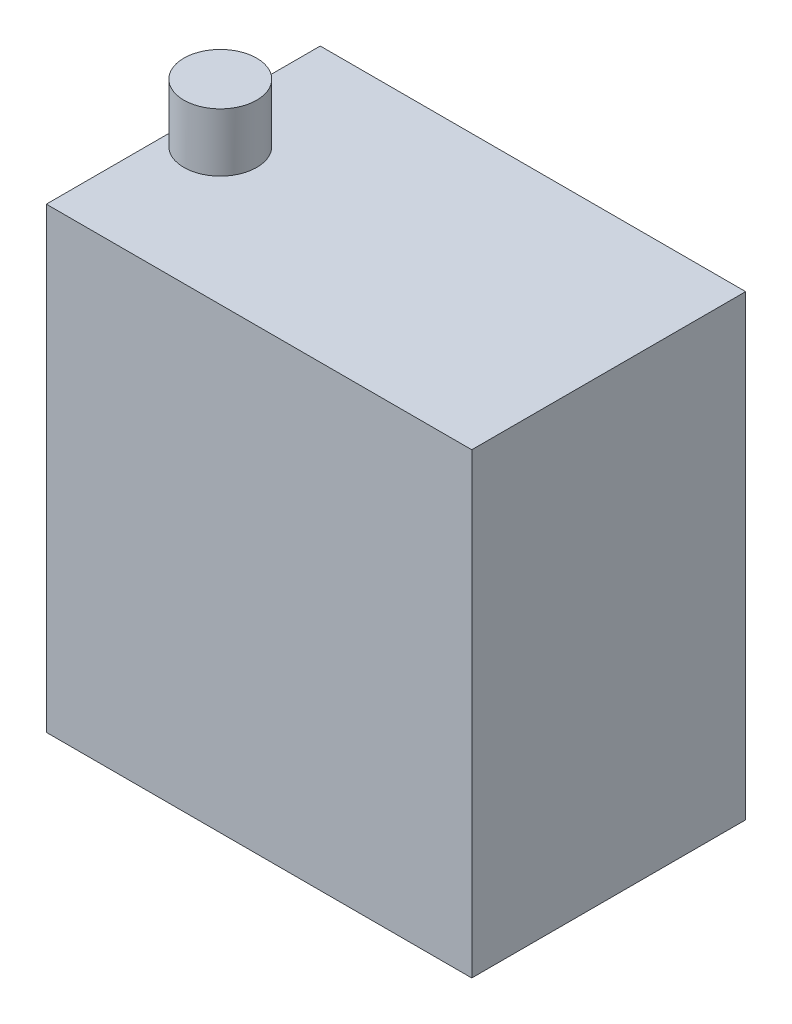
SolidWorks part; units mm, degrees
ref_plane "Front Plane" through (0, 0, 0) normal (0, 0, 1) x (1, 0, 0)
ref_plane "Top Plane" through (0, 0, 0) normal (0, 1, 0) x (1, 0, 0)
ref_plane "Right Plane" through (0, 0, 0) normal (1, 0, 0) x (0, 0, -1)
sketch "Sketch1" plane through (0, 0, 0) normal (0, 1, 0) x (1, 0, 0)
  line L1 (0, 0) -> (73, 0)
  line L2 (0, 0) -> (0, 47)
  line L3 (0, 47) -> (73, 47)
  line L4 (73, 0) -> (73, 47)
  dimension "D1" = 47
  dimension "D2" = 73
extrude "Boss-Extrude1" add sketch "Sketch1" along normal blind 78.5
sketch "Sketch2" plane through (0, 78.5, 0) normal (0, 1, 0) x (1, 0, 0)
  line L0 (0, 23.5) -> (73, 23.5) construction
  line L1 (0, 47) -> (0, 0) construction
  line L2 (73, 0) -> (73, 47) construction
  circle A0 centre (6.35, 23.5) radius 6.25
  dimension "D2" = 12.5
  dimension "D1" = 6.35
extrude "Boss-Extrude2" add sketch "Sketch2" along normal blind 10
sketch "Sketch3" plane through (0, 0, 0) normal (-1, 0, 0) x (0, 0, 1)
  line L0 (-23.5, 0) -> (-23.5, 78.5) construction
  line L1 (-47, 0) -> (0, 0) construction
  line L2 (-47, 78.5) -> (0, 78.5) construction
  line L3 (-23.5, 20) -> (-25.6706, 32.3101)
  line L4 (-23.5, 20) -> (-21.3294, 32.3101)
  line L5 (-23.5, 20) -> (-18.0204, 31.2349)
  line L6 (-23.5, 20) -> (-14.5083, 28.6832)
  line L7 (-23.5, 20) -> (-12.4632, 25.8684)
  line L8 (-23.5, 20) -> (-11.1216, 21.7397)
  line L9 (-23.5, 20) -> (-11.1216, 18.2603)
  line L10 (-23.5, 20) -> (-12.4632, 14.1316)
  line L11 (-23.5, 20) -> (-14.5083, 11.3168)
  line L12 (-23.5, 20) -> (-18.0204, 8.7651)
  line L13 (-23.5, 20) -> (-21.3294, 7.6899)
  line L14 (-23.5, 20) -> (-25.6706, 7.6899)
  line L15 (-23.5, 20) -> (-28.9796, 8.7651)
  line L16 (-23.5, 20) -> (-32.4917, 11.3168)
  line L17 (-23.5, 20) -> (-34.5368, 14.1316)
  line L18 (-23.5, 20) -> (-35.8784, 18.2603)
  line L19 (-23.5, 20) -> (-35.8784, 21.7397)
  line L20 (-23.5, 20) -> (-34.5368, 25.8684)
  line L21 (-23.5, 20) -> (-32.4917, 28.6832)
  line L22 (-23.5, 20) -> (-28.9796, 31.2349)
  circle A0 centre (-23.5, 20) radius 15
  circle A1 centre (-23.5, 20) radius 3.75
  circle A2 centre (-23.5, 20) radius 12.5
  point P33 (-23.5, 20)
  dimension "D1" = 30
  dimension "D3" = 7.5
  dimension "D4" = 25
  dimension "D2" = 20
  dimension "D5" = 10
  dimension "D6" = 10
extrude "Cut-Extrude1" cut sketch "Sketch3" against normal blind 10 contours L0 A1 L4 A2 | A1 L0 A2 L3 | L6 A2 L5 A1 | L8 A2 L7 A1 | L10 A2 L9 A1 | L12 A2 L11 A1 | L0 A2 L13 A1 | A2 L0 A1 L14 | L16 A2 L15 A1 | L18 A2 L17 A1 | L20 A2 L19 A1 | L22 A2 L21 A1
